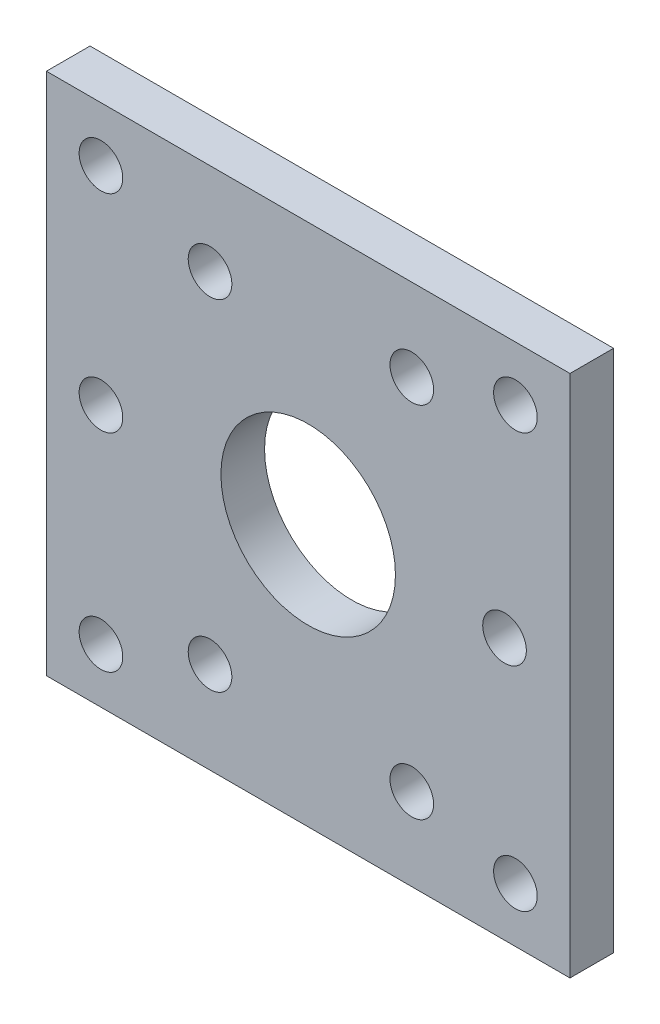
SolidWorks part; units mm, degrees
ref_plane "前视基准面" through (0, 0, 0) normal (0, 0, 1) x (1, 0, 0)
ref_plane "上视基准面" through (0, 0, 0) normal (0, 1, 0) x (1, 0, 0)
ref_plane "右视基准面" through (0, 0, 0) normal (1, 0, 0) x (0, 0, -1)
other "Configuration Table"
sketch "草图3" plane through (0, 0, 0) normal (0, 0, 1) x (1, 0, 0)
  line L1 (-30, -30) -> (30, -30)
  line L2 (-30, -30) -> (-30, 30)
  line L3 (-30, 30) -> (30, 30)
  line L4 (30, -30) -> (30, 30)
  line L5 (-30, -30) -> (30, 30) construction
  line L6 (-30, 30) -> (30, -30) construction
  circle A0 centre (0, 0) radius 10
  point P0 (0, 0)
  dimension "D3" = 20
  dimension "D1" = 60
  dimension "D2" = 60
extrude "凸台-拉伸2" add sketch "草图3" along normal blind 5
sketch "草图4" plane through (0, 0, 0) normal (0, 0, 1) x (1, 0, 0)
  line L0 (-1000, 0) -> (49000, 0) construction
  line L1 (0, -1000) -> (0, 49000) construction
  line L2 (0, 0) -> (25000, 43301.2702) construction
  line L3 (0, 0) -> (-25000, 43301.2702) construction
  line L5 (-23.75, -23.75) -> (23.75, -23.75) construction
  line L6 (-23.75, -23.75) -> (-23.75, 23.75) construction
  line L7 (-23.75, 23.75) -> (23.75, 23.75) construction
  line L8 (23.75, -23.75) -> (23.75, 23.75) construction
  line L9 (-23.75, -23.75) -> (23.75, 23.75) construction
  line L10 (-23.75, 23.75) -> (23.75, -23.75) construction
  circle A0 centre (0, 0) radius 22.5 construction
  circle A1 centre (0, 0) radius 23.75 construction
  circle A2 centre (11.875, 20.5681) radius 2.5
  circle A3 centre (22.5, 0) radius 2.5
  circle A4 centre (11.875, -20.5681) radius 2.5
  circle A5 centre (-11.25, -19.4856) radius 2.5
  circle A6 centre (-23.75, 0) radius 2.5
  circle A7 centre (-11.25, 19.4856) radius 2.5
  circle A8 centre (-23.75, 23.75) radius 2.5
  circle A9 centre (23.75, 23.75) radius 2.5
  circle A10 centre (23.75, -23.75) radius 2.5
  circle A11 centre (-23.75, -23.75) radius 2.5
  dimension "D3" = 45
  dimension "D4" = 47.5
  dimension "D5" = 5
  dimension "D6" = 5
  dimension "D7" = 5
  dimension "D8" = 5
  dimension "D9" = 5
  dimension "D10" = 5
  dimension "D13" = 5
  dimension "D14" = 5
  dimension "D15" = 5
  dimension "D16" = 5
  dimension "D1" = 30
  dimension "D2" = 30
  dimension "D11" = 47.5
  dimension "D12" = 47.5
extrude "切除-拉伸1" cut sketch "草图4" along normal up to surface (5 mm away) from surface at 0 up to face at (0, 0, 5) starting at face at (0, 0, 0)
